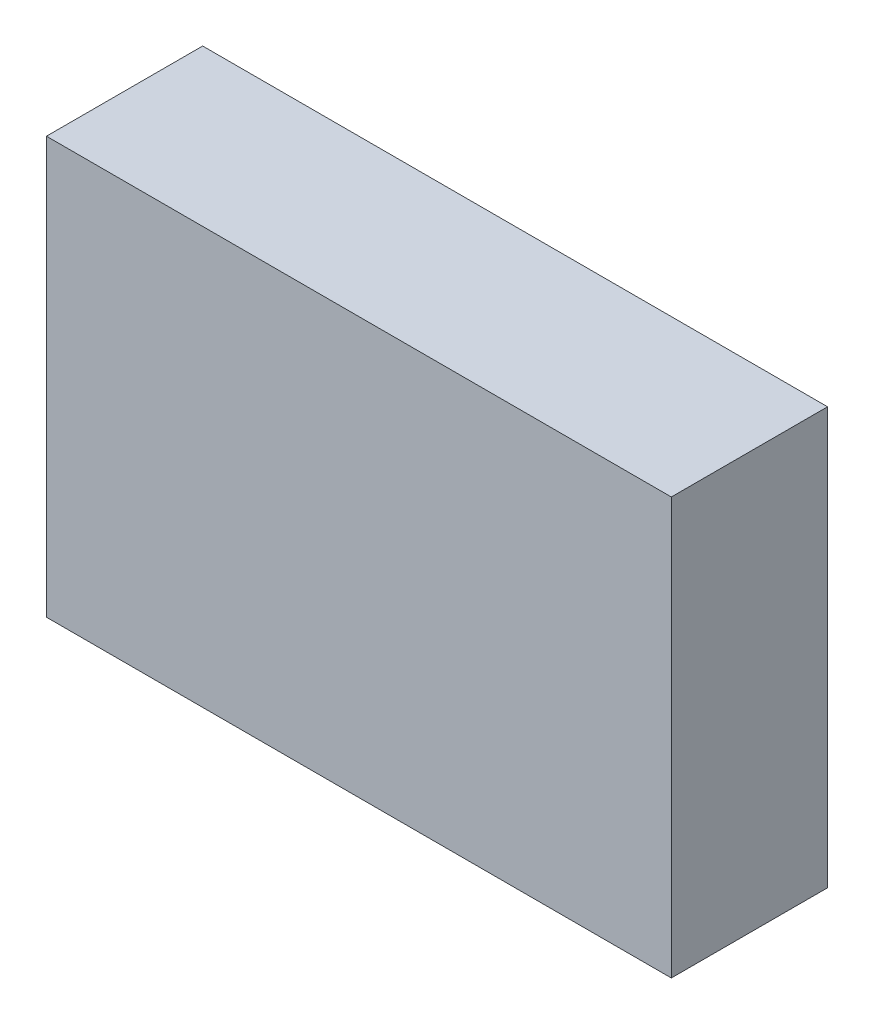
SolidWorks part; units mm, degrees
ref_plane "前基準面" through (0, 0, 0) normal (0, 0, 1) x (1, 0, 0)
ref_plane "上基準面" through (0, 0, 0) normal (0, 1, 0) x (1, 0, 0)
ref_plane "右基準面" through (0, 0, 0) normal (1, 0, 0) x (0, 0, -1)
sketch "草圖1" plane through (0, 0, 0) normal (0, 0, 1) x (1, 0, 0)
  line L1 (0, 0) -> (-60, 0)
  line L2 (0, 0) -> (0, 40)
  line L3 (0, 40) -> (-60, 40)
  line L4 (-60, 0) -> (-60, 40)
  dimension "D1" = 60
  dimension "D2" = 40
extrude "填料-伸長1" add sketch "草圖1" along normal blind 15
sketch "草圖2" plane through (0, 0, 0) normal (0, 0, -1) x (-1, 0, 0)
  line L0 (0, 40) -> (60, 40) construction
  line L1 (2, 38) -> (58, 38)
  line L2 (2, 38) -> (2, 2)
  line L3 (2, 2) -> (58, 2)
  line L4 (58, 38) -> (58, 2)
  line L5 (60, 40) -> (60, 0) construction
  line L6 (60, 0) -> (0, 0) construction
  line L7 (0, 0) -> (0, 40) construction
  dimension "D1" = 2
  dimension "D2" = 2
  dimension "D3" = 2
  dimension "D4" = 2
extrude "除料-伸長1" cut sketch "草圖2" against normal blind 13 contours L1 L4 L3 L2
